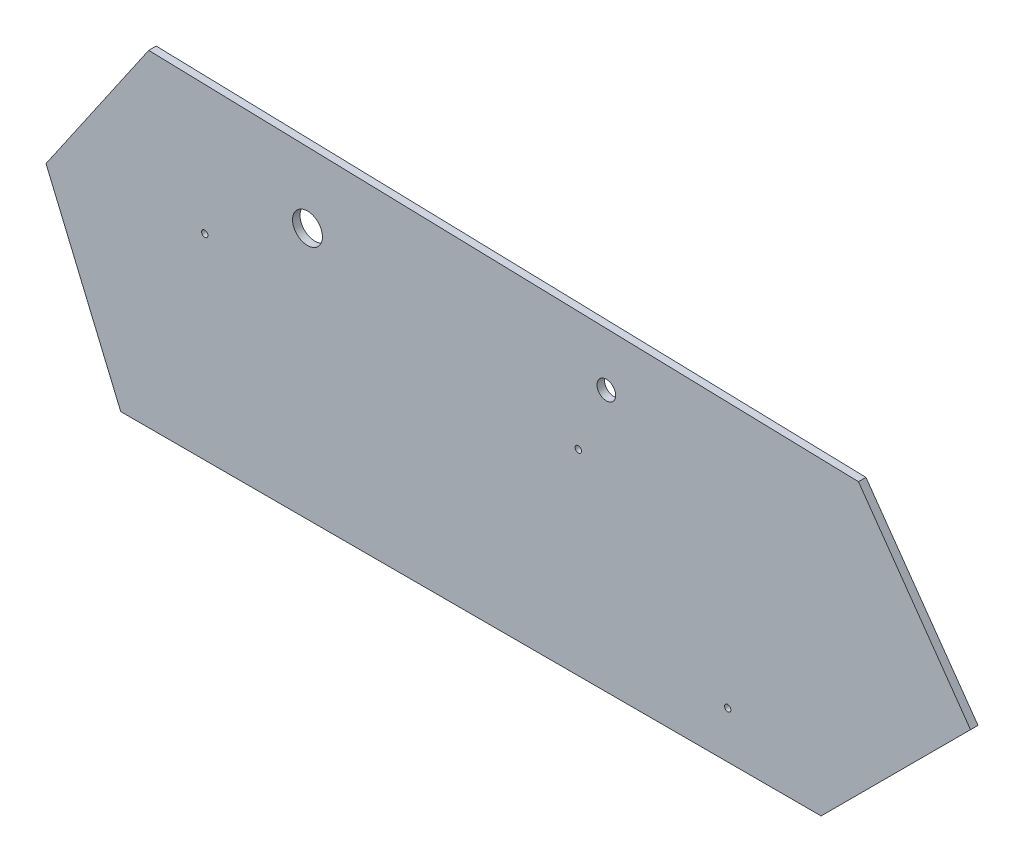
SolidWorks part; units mm, degrees
ref_plane "前视基准面" through (0, 0, 0) normal (0, 0, 1) x (1, 0, 0)
ref_plane "上视基准面" through (0, 0, 0) normal (0, 1, 0) x (1, 0, 0)
ref_plane "右视基准面" through (0, 0, 0) normal (1, 0, 0) x (0, 0, -1)
other "Configuration Table"
sketch "草图1" plane through (0, 0, 0) normal (0, 0, 1) x (1, 0, 0)
  line L0 (-125, -45) -> (250, -45)
  line L1 (250, -45) -> (330, 35)
  line L2 (330, 35) -> (270, 120)
  line L3 (270, 120) -> (-110, 130)
  line L4 (-110, 130) -> (-165, 50)
  line L5 (-165, 50) -> (-125, -45)
  circle A0 centre (-80, 60) radius 1.7
  circle A1 centre (120, 60) radius 1.7
  circle A2 centre (200, -20) radius 1.7
  circle A3 centre (-25, 90) radius 8
  circle A4 centre (135, 95) radius 5
extrude "凸台-拉伸1" add sketch "草图1" along normal blind 4
